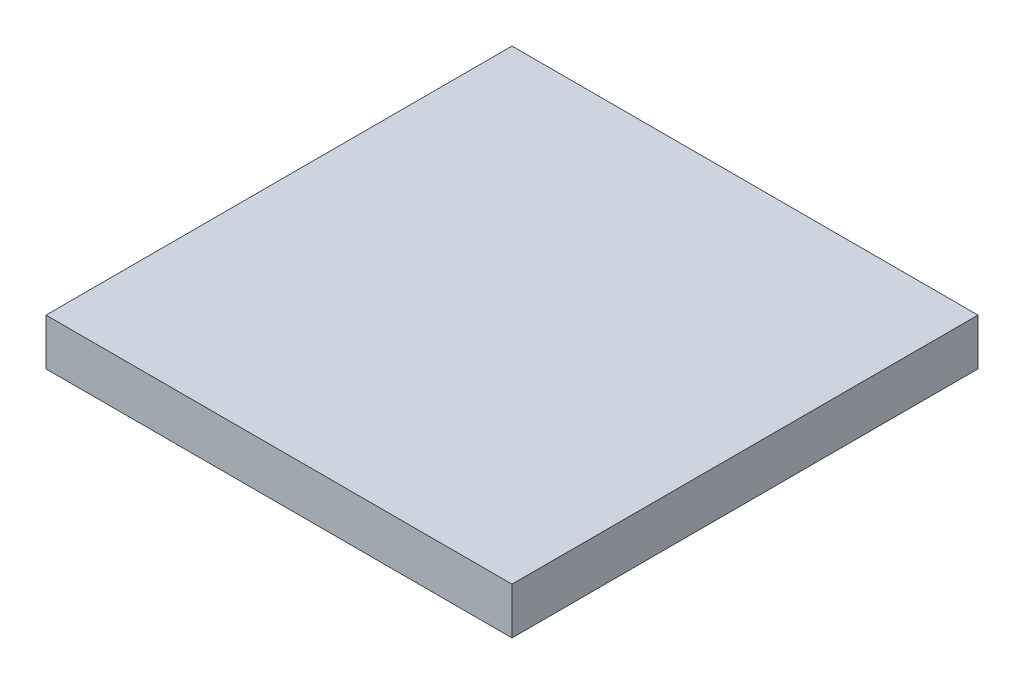
SolidWorks part; units mm, degrees
ref_plane "Front Plane" through (0, 0, 0) normal (0, 0, 1) x (1, 0, 0)
ref_plane "Top Plane" through (0, 0, 0) normal (0, 1, 0) x (1, 0, 0)
ref_plane "Right Plane" through (0, 0, 0) normal (1, 0, 0) x (0, 0, -1)
sketch "Sketch1" plane through (0, 0, 0) normal (0, 1, 0) x (1, 0, 0)
  line L1 (50, -50) -> (-50, -50)
  line L2 (50, -50) -> (50, 50)
  line L3 (50, 50) -> (-50, 50)
  line L4 (-50, -50) -> (-50, 50)
  line L5 (50, -50) -> (-50, 50) construction
  line L6 (50, 50) -> (-50, -50) construction
  point P0 (0, 0)
extrude "Boss-Extrude1" add sketch "Sketch1" along normal blind 10
